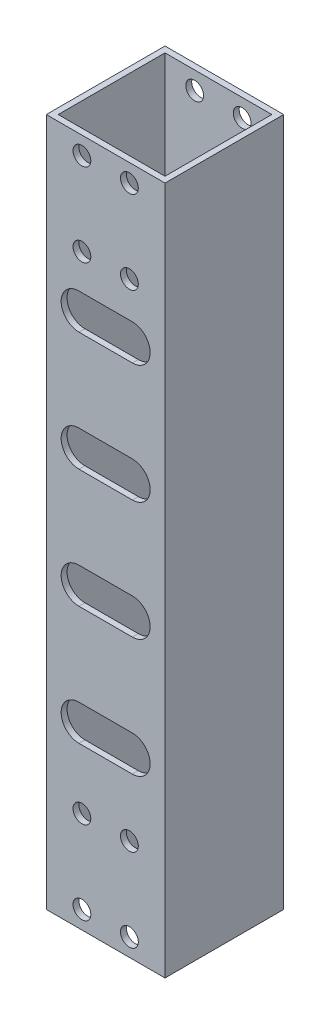
SolidWorks part; units mm, degrees
material "6061 合金"
ref_plane "前视基准面" through (0, 0, 0) normal (0, 0, 1) x (1, 0, 0)
ref_plane "上视基准面" through (0, 0, 0) normal (0, 1, 0) x (1, 0, 0)
ref_plane "右视基准面" through (0, 0, 0) normal (1, 0, 0) x (0, 0, -1)
sketch3d "3D草图1"
  line L0 (0, 0, 0) -> (0, 116, 0)
  dimension "D1" = 116
other "Hs 20X20X1(1)"
ref_plane "基准面1" through (0, 0, 0) normal (0, 1, 0) x (1, 0, 0)
sketch "草图1" plane through (0, 0, 0) normal (0, 1, 0) x (1, 0, 0)
  line L0 (-9, -9) -> (-9, 9)
  line L1 (-10, -10) -> (10, -10)
  line L2 (-10, -10) -> (-10, 10)
  line L3 (-10, 10) -> (10, 10)
  line L4 (10, -10) -> (10, 10)
  line L5 (-10, -10) -> (10, 10) construction
  line L6 (-10, 10) -> (10, -10) construction
  line L7 (-9, 9) -> (9, 9)
  line L8 (9, -9) -> (9, 9)
  line L9 (-9, -9) -> (9, -9)
  point P0 (0, 0)
  point P10 (0, 0)
  dimension "D1" = 1
sketch "草图4" plane through (0, 0, -10) normal (0, 0, -1) x (-1, 0, 0)
  line L0 (-4.5, 30) -> (4.5, 30) construction
  line L1 (-4.5, 33) -> (4.5, 33)
  line L2 (-4.5, 27) -> (4.5, 27)
  line L3 (-10, 0) -> (10, 0) construction
  line L4 (-10, 116) -> (-10, 0) construction
  arc A0 (-4.5, 33) -> (-4.5, 27) centre (-4.5, 30) ccw
  arc A1 (4.5, 27) -> (4.5, 33) centre (4.5, 30) ccw
  point P2 (0, 30)
  dimension "D1" = 3
  dimension "D2" = 9
  dimension "D3" = 30
  dimension "D4" = 10
extrude "切除-拉伸4" cut sketch "草图4" against normal blind 37
pattern_linear "阵列(线性)1" count 4 spacing 20 along (0, 1, 0) of "切除-拉伸4"
sketch "草图5" plane through (0, 0, -10) normal (0, 0, -1) x (-1, 0, 0)
  circle A0 centre (-4, 3) radius 1.5
  circle A1 centre (4, 3) radius 1.5
  circle A2 centre (4, 17) radius 1.5
  circle A3 centre (-4, 17) radius 1.5
  circle A4 centre (-4, 113) radius 1.5
  circle A5 centre (4, 113) radius 1.5
  circle A6 centre (-4, 99) radius 1.5
  circle A7 centre (4, 99) radius 1.5
  dimension "D1" = 3
  dimension "D2" = 3
  dimension "D3" = 3
  dimension "D4" = 3
  dimension "D5" = 3
  dimension "D6" = 3
  dimension "D7" = 3
  dimension "D8" = 3
extrude "切除-拉伸5" cut sketch "草图5" against normal blind 31
